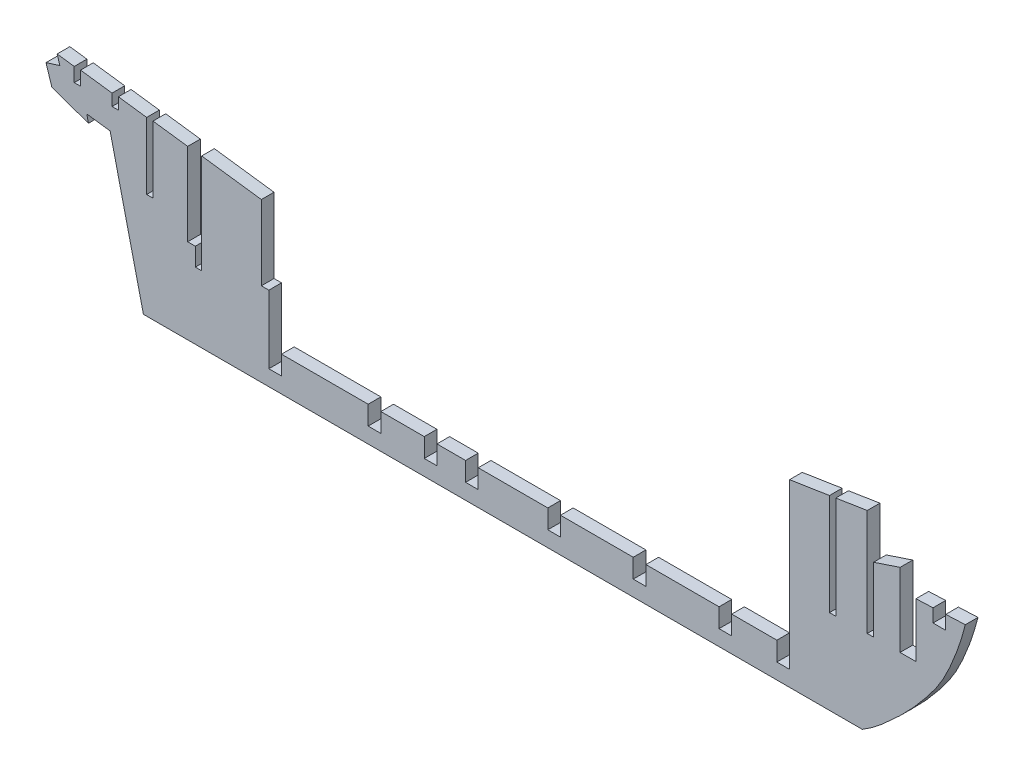
SolidWorks part; units mm, degrees
ref_plane "前视基准面" through (0, 0, 0) normal (0, 0, 1) x (1, 0, 0)
ref_plane "上视基准面" through (0, 0, 0) normal (0, 1, 0) x (1, 0, 0)
ref_plane "右视基准面" through (0, 0, 0) normal (1, 0, 0) x (0, 0, -1)
other "Configuration Table"
sketch "草图1" plane through (0, 0, 0) normal (0, 0, 1) x (1, 0, 0)
  line L0 (130.1027, 142.0525) -> (769.026, -255.797) construction
  line L1 (0, 0) -> (453.5405, 0)
  line L2 (0, 0) -> (-21.0207, 89.6799)
  line L3 (-21.0207, 89.6799) -> (-35.7526, 91.6319)
  line L4 (-35.7526, 91.6319) -> (-34.6764, 87.0403)
  line L5 (-34.6764, 87.0403) -> (-57.7792, 95.1746)
  line L6 (-57.7792, 95.1746) -> (-61.4683, 106.7945)
  line L7 (-61.4683, 106.7945) -> (-52.7088, 109.5754)
  line L8 (-52.7088, 109.5754) -> (-54.4449, 115.044)
  line L9 (-54.4449, 115.044) -> (-43.6607, 113.6151)
  line L10 (-43.6607, 113.6151) -> (-43.6607, 104.77)
  line L11 (-43.6607, 104.77) -> (-39.6607, 104.77)
  line L12 (-39.6607, 104.77) -> (-39.6607, 113.6151)
  line L13 (-39.6607, 113.6151) -> (-19.7929, 110.9827)
  line L14 (-19.7929, 110.9827) -> (-19.7929, 103.6489)
  line L15 (-19.7929, 103.6489) -> (-15.7929, 103.6489)
  line L16 (-15.7929, 103.6489) -> (-15.7929, 110.9827)
  line L17 (-15.7929, 110.9827) -> (2.0373, 108.6202)
  line L18 (2.0373, 108.6202) -> (2.0373, 66.5029)
  line L19 (2.0373, 66.5029) -> (6.0373, 66.5029)
  line L20 (6.0373, 66.5029) -> (6.0373, 108.6202)
  line L21 (6.0373, 108.6202) -> (27.9054, 105.7227)
  line L22 (27.9054, 105.7227) -> (27.9054, 53.5885)
  line L23 (27.9054, 53.5885) -> (32.7323, 53.5885)
  line L24 (32.7323, 53.5885) -> (32.7323, 42.1646)
  line L25 (32.7323, 42.1646) -> (36.7323, 42.1646)
  line L26 (36.7323, 42.1646) -> (36.7323, 104.9122)
  line L27 (36.7323, 104.9122) -> (74.3942, 99.9221)
  line L28 (74.3942, 99.9221) -> (74.3942, 52.776)
  line L29 (74.3942, 52.776) -> (79.1286, 52.776)
  line L30 (79.1286, 52.776) -> (79.1286, 9.8332)
  line L31 (79.1286, 9.8332) -> (87.1286, 9.8332)
  line L32 (87.1286, 9.8332) -> (87.1286, 21.789)
  line L33 (87.1286, 21.789) -> (141.7855, 21.789)
  line L34 (141.7855, 21.789) -> (141.7855, 9.8332)
  line L35 (141.7855, 9.8332) -> (149.7855, 9.8332)
  line L36 (149.7855, 9.8332) -> (149.7855, 21.789)
  line L37 (149.7855, 21.789) -> (177.1706, 21.789)
  line L38 (177.1706, 21.789) -> (177.1706, 9.8332)
  line L39 (177.1706, 9.8332) -> (185.1706, 9.8332)
  line L40 (185.1706, 9.8332) -> (185.1706, 21.789)
  line L41 (185.1706, 21.789) -> (203.2379, 21.789)
  line L42 (203.2379, 21.789) -> (203.2379, 9.8332)
  line L43 (203.2379, 9.8332) -> (211.2379, 9.8332)
  line L44 (211.2379, 9.8332) -> (211.2379, 21.789)
  line L45 (211.2379, 21.789) -> (255.112, 21.789)
  line L46 (255.112, 21.789) -> (255.112, 9.8332)
  line L47 (255.112, 9.8332) -> (263.112, 9.8332)
  line L48 (263.112, 9.8332) -> (263.112, 21.789)
  line L49 (263.112, 21.789) -> (309.0137, 21.789)
  line L50 (309.0137, 21.789) -> (309.0137, 9.8332)
  line L51 (309.0137, 9.8332) -> (317.0137, 9.8332)
  line L52 (317.0137, 9.8332) -> (317.0137, 21.789)
  line L53 (317.0137, 21.789) -> (363.1497, 21.789)
  line L54 (363.1497, 21.789) -> (363.1497, 9.8332)
  line L55 (363.1497, 9.8332) -> (371.1497, 9.8332)
  line L56 (371.1497, 9.8332) -> (371.1497, 21.789)
  line L60 (407.6295, 9.8332) -> (407.6295, 113.4745)
  line L61 (407.6295, 113.4745) -> (432.8245, 117.4203)
  line L62 (432.8245, 117.4203) -> (432.8245, 53.4435)
  line L63 (432.8245, 53.4435) -> (436.8245, 53.4435)
  line L64 (436.8245, 53.4435) -> (436.8245, 118.0468)
  line L65 (436.8245, 118.0468) -> (456.6515, 121.1519)
  line L66 (456.6515, 121.1519) -> (456.6515, 53.9576)
  line L67 (456.6515, 53.9576) -> (460.6515, 53.9576)
  line L68 (460.6515, 53.9576) -> (460.6515, 94.8762)
  line L69 (460.6515, 94.8762) -> (477.3707, 100.4362)
  line L70 (477.3707, 100.4362) -> (477.3707, 53.9576)
  line L71 (477.3707, 53.9576) -> (487.3707, 53.9576)
  line L72 (487.3707, 53.9576) -> (487.3707, 88.2955)
  line L73 (487.3707, 88.2955) -> (498.162, 88.7644)
  line L74 (498.162, 88.7644) -> (498.162, 80.4195)
  line L75 (498.162, 80.4195) -> (506.162, 80.4195)
  line L76 (506.162, 80.4195) -> (506.162, 89.1424)
  line L77 (506.162, 89.1424) -> (518.5317, 89.6799)
  line L78 (-1607.1012, 845.6507) -> (-854.4346, 845.6507) construction
  line L79 (371.1497, 21.789) -> (399.6295, 21.789)
  line L80 (399.6295, 21.789) -> (399.6295, 9.8332)
  line L81 (399.6295, 9.8332) -> (407.6295, 9.8332)
  spline S0 degree 3 poles (453.5405, 0) (460.7901, 4.21) (469.5699, 12.0723) (483.6222, 25.2848) (493.1974, 36.4341) (502.6958, 49.1893) (511.2061, 65.7294) (516.0297, 79.8313) (518.5317, 89.6799) knots 0 0 0 0 0.219529 0.311377 0.509995 0.607273 0.731274 1 1 1 1
  dimension "D19" = 113.4952
  dimension "D1" = 8
  dimension "D2" = 10
  dimension "D3" = 4
  dimension "D4" = 4
  dimension "D5" = 4
  dimension "D6" = 8
  dimension "D7" = 580
  dimension "D18" = 453.5405
extrude "凸台-拉伸1" add sketch "草图1" along normal blind 8
